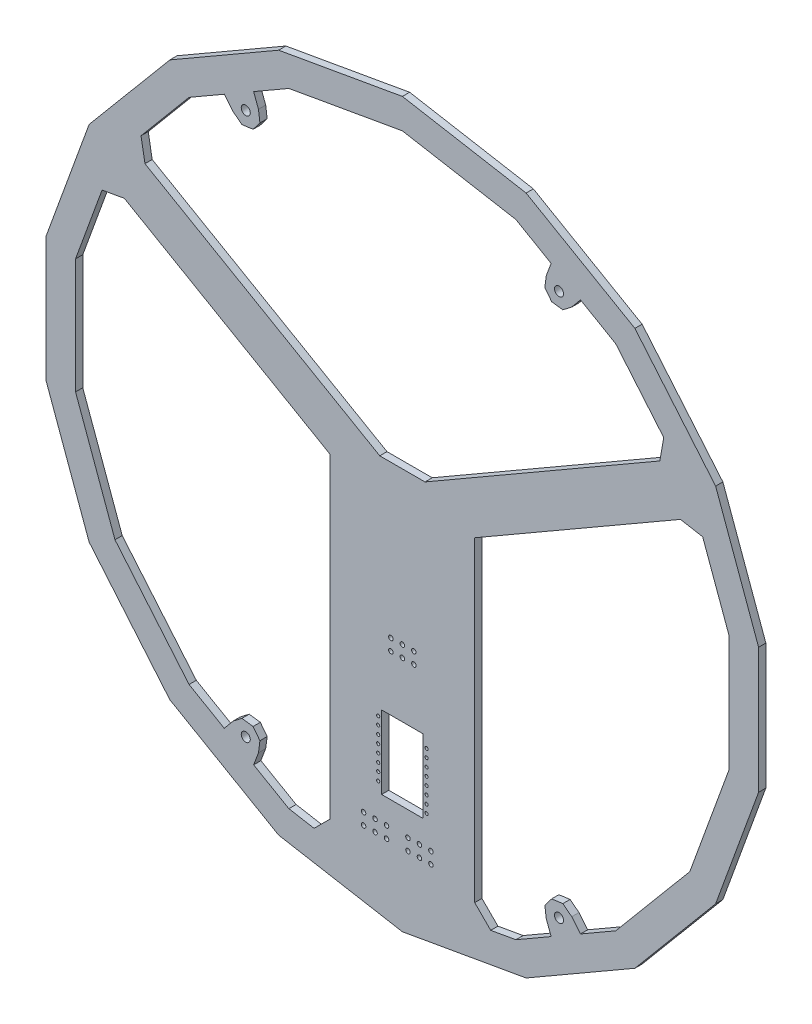
SolidWorks part; units mm, degrees
ref_plane "Front Plane" through (0, 0, 0) normal (0, 0, 1) x (1, 0, 0)
ref_plane "Top Plane" through (0, 0, 0) normal (0, 1, 0) x (1, 0, 0)
ref_plane "Right Plane" through (0, 0, 0) normal (1, 0, 0) x (0, 0, -1)
sketch "Model" plane through (0, 0, 0) normal (0, 0, 1) x (1, 0, 0)
  line L0 (-78.7846, -13.8919) -> (-69.282, -40)
  line L1 (-69.282, -40) -> (-51.423, -61.2836)
  line L2 (-51.423, -61.2836) -> (-27.3616, -75.1754)
  line L3 (-27.3616, -75.1754) -> (0, -80)
  line L4 (0, -80) -> (27.3616, -75.1754)
  line L5 (27.3616, -75.1754) -> (51.423, -61.2836)
  line L6 (51.423, -61.2836) -> (69.282, -40)
  line L7 (69.282, -40) -> (78.7846, -13.8919)
  line L8 (78.7846, -13.8919) -> (78.7846, 13.8919)
  line L9 (78.7846, 13.8919) -> (69.282, 40)
  line L10 (69.282, 40) -> (51.423, 61.2836)
  line L11 (51.423, 61.2836) -> (27.3616, 75.1754)
  line L12 (27.3616, 75.1754) -> (0, 80)
  line L13 (0, 80) -> (-27.3616, 75.1754)
  line L14 (-27.3616, 75.1754) -> (-51.423, 61.2836)
  line L15 (-51.423, 61.2836) -> (-69.282, 40)
  line L16 (-69.282, 40) -> (-78.7846, 13.8919)
  line L17 (-78.7846, 13.8919) -> (-78.7846, -13.8919)
  line L18 (-4.6, -56) -> (4.6, -56)
  line L19 (4.6, -56) -> (4.6, -39.8)
  line L20 (4.6, -39.8) -> (-4.6, -39.8)
  line L21 (-4.6, -39.8) -> (-4.6, -56)
  line L22 (-72.2846, -12.7457) -> (-63.566, -36.6999)
  line L23 (-63.566, -36.6999) -> (-47.1804, -56.2275)
  line L24 (-47.1804, -56.2275) -> (-39.3899, -60.7253)
  line L25 (-39.3899, -60.7253) -> (-37.4545, -58.3787)
  line L26 (-37.4545, -58.3787) -> (-35.4827, -56.8657)
  line L27 (-35.4827, -56.8657) -> (-33.0187, -57.1901)
  line L28 (-33.0187, -57.1901) -> (-31.5058, -59.1618)
  line L29 (-31.5058, -59.1618) -> (-31.8302, -61.6258)
  line L30 (-31.8302, -61.6258) -> (-32.8947, -64.4753)
  line L31 (-32.8947, -64.4753) -> (-25.1042, -68.9732)
  line L32 (-25.1042, -68.9732) -> (-19.5355, -69.9551)
  line L33 (-19.5355, -69.9551) -> (-16, -66.4196)
  line L34 (-16, -66.4196) -> (-16, 3.4641)
  line L35 (-16, 3.4641) -> (-61.4947, 29.7305)
  line L36 (-61.4947, 29.7305) -> (-66.4187, 28.8622)
  line L37 (-66.4187, 28.8622) -> (-72.2846, 12.7457)
  line L38 (-72.2846, 12.7457) -> (-72.2846, -12.7457)
  line L39 (16, -66.4196) -> (19.5355, -69.9551)
  line L40 (19.5355, -69.9551) -> (25.1042, -68.9732)
  line L41 (25.1042, -68.9732) -> (32.8947, -64.4753)
  line L42 (32.8947, -64.4753) -> (31.8302, -61.6258)
  line L43 (31.8302, -61.6258) -> (31.5058, -59.1618)
  line L44 (31.5058, -59.1618) -> (33.0187, -57.1901)
  line L45 (33.0187, -57.1901) -> (35.4827, -56.8657)
  line L46 (35.4827, -56.8657) -> (37.4545, -58.3787)
  line L47 (37.4545, -58.3787) -> (39.3899, -60.7253)
  line L48 (39.3899, -60.7253) -> (47.1804, -56.2275)
  line L49 (47.1804, -56.2275) -> (63.566, -36.6999)
  line L50 (63.566, -36.6999) -> (72.2846, -12.7457)
  line L51 (72.2846, -12.7457) -> (72.2846, 12.7457)
  line L52 (72.2846, 12.7457) -> (66.4187, 28.8622)
  line L53 (66.4187, 28.8622) -> (61.4947, 29.7305)
  line L54 (61.4947, 29.7305) -> (16, 3.4641)
  line L55 (16, 3.4641) -> (16, -66.4196)
  line L56 (-57.8025, 43.5686) -> (-56.9343, 38.6445)
  line L57 (-56.9343, 38.6445) -> (-5, 8.6602)
  line L58 (-5, 8.6602) -> (5, 8.6602)
  line L59 (5, 8.6602) -> (56.9343, 38.6445)
  line L60 (56.9343, 38.6445) -> (57.8025, 43.5686)
  line L61 (57.8025, 43.5686) -> (47.1804, 56.2275)
  line L62 (47.1804, 56.2275) -> (39.3899, 60.7253)
  line L63 (39.3899, 60.7253) -> (37.4545, 58.3787)
  line L64 (37.4545, 58.3787) -> (35.4827, 56.8657)
  line L65 (35.4827, 56.8657) -> (33.0187, 57.1901)
  line L66 (33.0187, 57.1901) -> (31.5058, 59.1618)
  line L67 (31.5058, 59.1618) -> (31.8302, 61.6258)
  line L68 (31.8302, 61.6258) -> (32.8947, 64.4753)
  line L69 (32.8947, 64.4753) -> (25.1042, 68.9732)
  line L70 (25.1042, 68.9732) -> (0, 73.3997)
  line L71 (0, 73.3997) -> (-25.1042, 68.9732)
  line L72 (-25.1042, 68.9732) -> (-32.8947, 64.4753)
  line L73 (-32.8947, 64.4753) -> (-31.8302, 61.6258)
  line L74 (-31.8302, 61.6258) -> (-31.5058, 59.1618)
  line L75 (-31.5058, 59.1618) -> (-33.0187, 57.1901)
  line L76 (-33.0187, 57.1901) -> (-35.4827, 56.8657)
  line L77 (-35.4827, 56.8657) -> (-37.4545, 58.3787)
  line L78 (-37.4545, 58.3787) -> (-39.3899, 60.7253)
  line L79 (-39.3899, 60.7253) -> (-47.1804, 56.2275)
  line L80 (-47.1804, 56.2275) -> (-57.8025, 43.5686)
  circle A0 centre (34.64, -60) radius 1
  circle A1 centre (-34.64, 60.01) radius 1
  circle A2 centre (34.65, 60) radius 1
  circle A3 centre (-34.64, -60) radius 1
  circle A4 centre (6.3176, -61.378) radius 0.5
  circle A5 centre (6.3176, -63.918) radius 0.5
  circle A6 centre (3.7776, -63.918) radius 0.5
  circle A7 centre (1.2376, -63.918) radius 0.5
  circle A8 centre (2.5374, -27.5374) radius 0.5
  circle A9 centre (-0.0026, -27.5374) radius 0.5
  circle A10 centre (-2.5426, -27.5374) radius 0.5
  circle A11 centre (-2.5426, -24.9974) radius 0.5
  circle A12 centre (2.5374, -24.9974) radius 0.5
  circle A13 centre (-3.5074, -63.9222) radius 0.5
  circle A14 centre (-6.0474, -63.9222) radius 0.5
  circle A15 centre (-8.5874, -63.9222) radius 0.5
  circle A16 centre (-8.5874, -61.3822) radius 0.5
  circle A17 centre (-6.0474, -61.3822) radius 0.5
  circle A18 centre (-3.5074, -61.3822) radius 0.5
  circle A19 centre (-0.0026, -24.9974) radius 0.5
  circle A20 centre (1.2376, -61.378) radius 0.5
  circle A21 centre (3.7776, -61.378) radius 0.5
  circle A22 centre (-5.35, -43.105) radius 0.35
  circle A23 centre (-5.35, -44.885) radius 0.35
  circle A24 centre (-5.35, -46.665) radius 0.35
  circle A25 centre (-5.35, -48.445) radius 0.35
  circle A26 centre (-5.35, -50.225) radius 0.35
  circle A27 centre (-5.35, -52.005) radius 0.35
  circle A28 centre (-5.35, -53.785) radius 0.35
  circle A29 centre (5.35, -54.675) radius 0.35
  circle A30 centre (5.35, -52.895) radius 0.35
  circle A31 centre (5.35, -51.115) radius 0.35
  circle A32 centre (5.35, -49.335) radius 0.35
  circle A33 centre (5.35, -47.555) radius 0.35
  circle A34 centre (5.35, -45.775) radius 0.35
  circle A35 centre (5.35, -43.995) radius 0.35
  circle A36 centre (-5.35, -41.325) radius 0.35
  circle A37 centre (5.35, -42.215) radius 0.35
extrude "Boss-Extrude1" add sketch "Model" along normal blind 1.6
